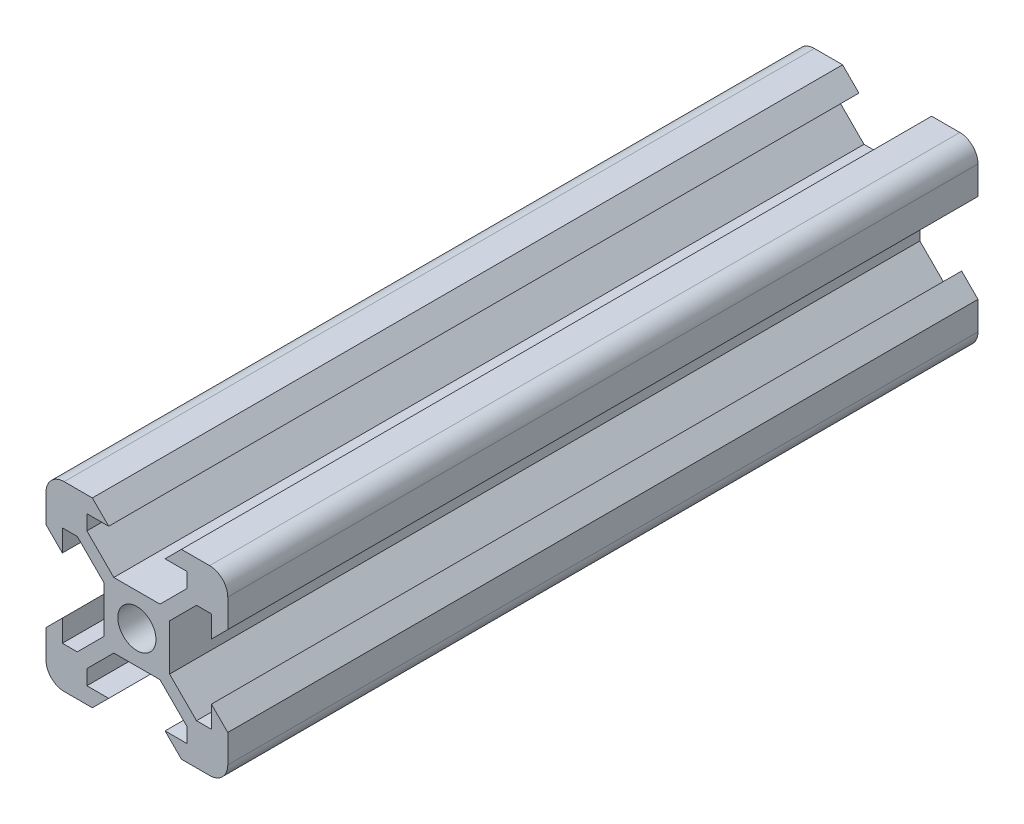
SolidWorks part; units mm, degrees
material "6061 Alloy"
ref_plane "Front Plane" through (0, 0, 0) normal (0, 0, 1) x (1, 0, 0)
ref_plane "Top Plane" through (0, 0, 0) normal (0, 1, 0) x (1, 0, 0)
ref_plane "Right Plane" through (0, 0, 0) normal (1, 0, 0) x (0, 0, -1)
sketch "Sketch1" plane through (0, 0, 0) normal (0, 0, 1) x (1, 0, 0)
  line L0 (-4.9, -10) -> (-5.5, -10)
  line L1 (-10, -10) -> (10, -10) construction
  line L2 (-10, -10) -> (-10, 10) construction
  line L3 (-10, 10) -> (10, 10) construction
  line L4 (10, -10) -> (10, 10) construction
  line L5 (-10, -10) -> (10, 10) construction
  line L6 (-10, 10) -> (10, -10) construction
  line L7 (-3.6, 3.6) -> (3.6, 3.6)
  line L8 (-3.6, 3.6) -> (-3.6, -3.6)
  line L9 (-3.6, -3.6) -> (3.6, -3.6)
  line L10 (3.6, 3.6) -> (3.6, -3.6)
  line L11 (-8, 10) -> (-5.5, 10)
  line L12 (-10, 8) -> (-10, 5.5)
  line L13 (-10, 5.5) -> (-5.5, 5.5)
  line L14 (-5.5, 10) -> (-5.5, 5.5)
  line L15 (8, 10) -> (5.5, 10)
  line L16 (10, 8) -> (10, 5.5)
  line L17 (10, 5.5) -> (5.5, 5.5)
  line L18 (5.5, 10) -> (5.5, 5.5)
  line L19 (8, -10) -> (5.5, -10)
  line L20 (10, -8) -> (10, -5.5)
  line L21 (10, -5.5) -> (5.5, -5.5)
  line L22 (5.5, -10) -> (5.5, -5.5)
  line L23 (-8, -10) -> (-5.5, -10)
  line L24 (-10, -8) -> (-10, -5.5)
  line L25 (-10, -5.5) -> (-5.5, -5.5)
  line L26 (-5.5, -10) -> (-5.5, -5.5)
  line L27 (-3.1, -8.2) -> (-4.9, -10)
  line L28 (-3.1, -8.2) -> (-5.5, -8.2)
  line L29 (4.9, -10) -> (5.5, -10)
  line L30 (3.1, -8.2) -> (4.9, -10)
  line L31 (3.1, -8.2) -> (5.5, -8.2)
  line L32 (-4.9, 10) -> (-5.5, 10)
  line L33 (-3.1, 8.2) -> (-4.9, 10)
  line L34 (-3.1, 8.2) -> (-5.5, 8.2)
  line L35 (4.9, 10) -> (5.5, 10)
  line L36 (0, 0) -> (17.4618, 0) construction
  line L37 (3.1, 8.2) -> (4.9, 10)
  line L38 (3.1, 8.2) -> (5.5, 8.2)
  line L39 (8.2, 3.1) -> (8.2, 5.5)
  line L40 (8.2, 3.1) -> (10, 4.9)
  line L41 (10, 4.9) -> (10, 5.5)
  line L42 (10, -4.9) -> (10, -5.5)
  line L43 (8.2, -3.1) -> (10, -4.9)
  line L44 (8.2, -3.1) -> (8.2, -5.5)
  line L57 (-8.2, -3.1) -> (-10, -4.9)
  line L58 (-10, -4.9) -> (-10, -5.5)
  line L61 (-8.2, -3.1) -> (-8.2, -5.5)
  line L62 (-8.2, 3.1) -> (-10, 4.9)
  line L63 (-10, 4.9) -> (-10, 5.5)
  line L66 (-8.2, 3.1) -> (-8.2, 5.5)
  line L67 (-2.7729, 2.7729) -> (-6.4508, 6.4508) construction
  line L68 (-2.2426, 3.3033) -> (-5.9205, 6.9812)
  line L69 (-3.3033, 2.2426) -> (-6.9812, 5.9205)
  line L70 (6.7372, 6.7372) -> (2.7729, 2.7729)
  line L71 (6.309, -6.309) -> (2.7729, -2.7729)
  line L72 (-2.8687, -2.8687) -> (-6.5971, -6.5971)
  line L73 (6.2069, 7.2675) -> (2.2426, 3.3033)
  line L74 (6.8393, -5.7786) -> (3.3033, -2.2426)
  line L75 (-3.399, -2.3384) -> (-7.1274, -6.0667)
  line L76 (7.2675, 6.2069) -> (3.3033, 2.2426)
  line L77 (5.7786, -6.8393) -> (2.2426, -3.3033)
  line L78 (-2.3384, -3.399) -> (-6.0667, -7.1274)
  circle A0 centre (0, 0) radius 2.1
  arc A1 (-8, -10) -> (-10, -8) centre (-8, -8) cw
  arc A2 (8, -10) -> (10, -8) centre (8, -8) ccw
  arc A3 (8, 10) -> (10, 8) centre (8, 8) cw
  arc A4 (-8, 10) -> (-10, 8) centre (-8, 8) ccw
  point P0 (0, 0)
  dimension "D3" = 4.2
  dimension "D12" = 2
  dimension "D1" = 20
  dimension "D4" = 6.4
  dimension "D5" = 6.4
  dimension "D6" = 6.4
  dimension "D7" = 6.4
  dimension "D8" = 4.5
  dimension "D9" = 4.5
  dimension "D10" = 4.5
  dimension "D11" = 4.5
  dimension "D13" = 45
  dimension "D19" = 45
  dimension "D20" = 6.2
  dimension "D23" = 1.8
  dimension "D24" = 1.8
  dimension "D28" = 0.75
  dimension "D26" = 0.75
  dimension "D27" = 0.75
  dimension "D29" = 0.75
extrude "Boss-Extrude1" add sketch "Sketch1" along normal blind 82.55
